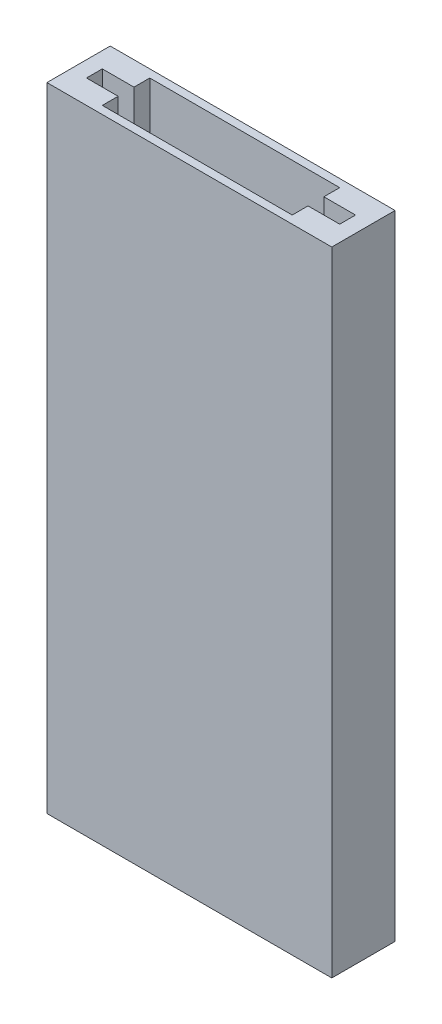
SolidWorks part; units mm, degrees
material "ABS"
ref_plane "Front" through (0, 0, 0) normal (0, 0, 1) x (1, 0, 0)
ref_plane "Top" through (0, 0, 0) normal (0, 1, 0) x (1, 0, 0)
ref_plane "Right" through (0, 0, 0) normal (1, 0, 0) x (0, 0, -1)
sketch "Sketch1" plane through (0, 0, 0) normal (0, 0, 1) x (1, 0, 0)
  line L1 (-28.575, 63.5) -> (28.575, 63.5)
  line L2 (-28.575, 63.5) -> (-28.575, -63.5)
  line L3 (-28.575, -63.5) -> (28.575, -63.5)
  line L4 (28.575, 63.5) -> (28.575, -63.5)
  line L5 (-28.575, 63.5) -> (28.575, -63.5) construction
  line L6 (-28.575, -63.5) -> (28.575, 63.5) construction
  point P0 (0, 0)
  dimension "D1" = 57.15
  dimension "D2" = 127
extrude "Boss-Extrude1" add sketch "Sketch1" along normal mid plane 12.7
sketch "Sketch2" plane through (0, 0, 0) normal (0, 0, 1) x (1, 0, 0)
  line L0 (28.575, 63.5) -> (-28.575, 63.5) construction
  line L1 (25.4, 63.5) -> (-25.4, 63.5)
  line L2 (25.4, 63.5) -> (25.4, -57.15)
  line L3 (25.4, -57.15) -> (-25.4, -57.15)
  line L4 (-25.4, 63.5) -> (-25.4, -57.15)
  line L5 (-28.575, -63.5) -> (28.575, -63.5) construction
  point P6 (0, -63.5)
  point P7 (0, -57.15)
  point P10 (0, 0)
  dimension "D1" = 50.8
  dimension "D2" = 6.35
extrude "Cut-Extrude1" cut sketch "Sketch2" against normal mid plane 3.175
sketch "Sketch3" plane through (0, 0, 0) normal (0, 0, 1) x (1, 0, 0)
  line L0 (28.575, 63.5) -> (-28.575, 63.5) construction
  line L1 (19.05, 63.5) -> (-19.05, 63.5)
  line L2 (19.05, 63.5) -> (19.05, 19.05)
  line L3 (19.05, 19.05) -> (-19.05, 19.05)
  line L4 (-19.05, 63.5) -> (-19.05, 19.05)
  line L5 (-28.575, -63.5) -> (28.575, -63.5) construction
  line L6 (25.4, -57.15) -> (-25.4, -57.15) construction
  point P6 (0, -63.5)
  point P7 (0, 19.05)
  point P10 (0, 0)
  dimension "D1" = 38.1
  dimension "D2" = 76.2
extrude "Cut-Extrude2" cut sketch "Sketch3" against normal mid plane 9.525
